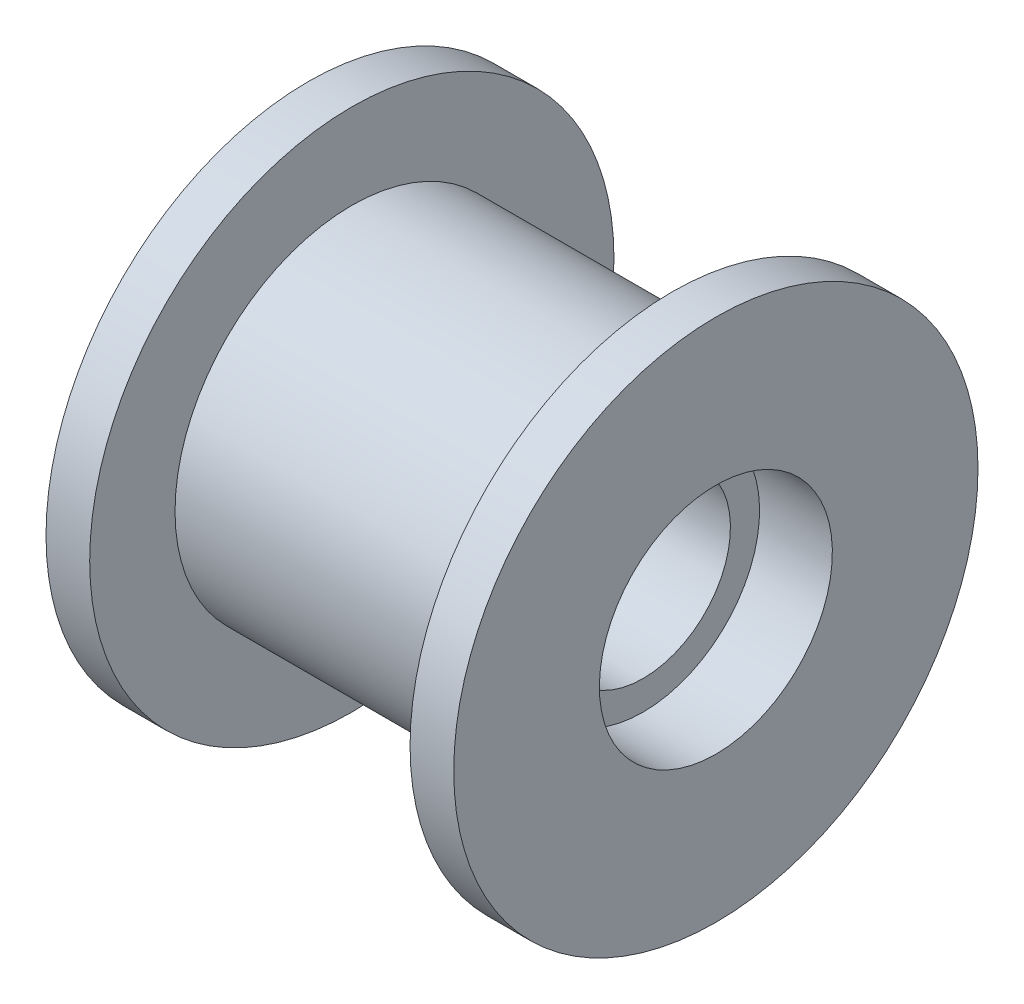
SolidWorks part; units mm, degrees
material "6061 Alloy"
ref_plane "Front Plane" through (0, 0, 0) normal (0, 0, 1) x (1, 0, 0)
ref_plane "Top Plane" through (0, 0, 0) normal (0, 1, 0) x (1, 0, 0)
ref_plane "Right Plane" through (0, 0, 0) normal (1, 0, 0) x (0, 0, -1)
sketch "Sketch1" plane through (0, 0, 0) normal (0, 0, 1) x (1, 0, 0)
  line L0 (-7, 0) -> (-7, 9)
  line L1 (-7, 9) -> (-5.5, 9)
  line L2 (-5.5, 9) -> (-5.5, 6.07)
  line L3 (-5.5, 6.07) -> (5.5, 6.07)
  line L4 (5.5, 6.07) -> (5.5, 9)
  line L5 (5.5, 9) -> (7, 9)
  line L6 (7, 9) -> (7, 0)
  line L7 (7, 0) -> (-7, 0)
  point P8 (0, 0)
  dimension "D1" = 9
  dimension "D2" = 1.5
  dimension "D3" = 2.93
  dimension "D4" = 11
  dimension "D5" = 1.5
revolve "Revolve1" add sketch "Sketch1" angle 360 about L7
sketch "Sketch3" plane through (7, 0, 0) normal (1, 0, 0) x (0, 0, -1)
  circle A0 centre (0, 0) radius 3
  dimension "D1" = 6
extrude "Cut-Extrude2" cut sketch "Sketch3" against normal through all both and the other way through all
sketch "Sketch2" plane through (-7, 0, 18.2091) normal (-1, 0, 0) x (0, 0, 1)
  circle A0 centre (-18.2091, 0) radius 4
  dimension "D1" = 8
extrude "Cut-Extrude1" cut sketch "Sketch2" against normal blind 2.5
sketch "Sketch4" plane through (7, 0, 11.2091) normal (-1, 0, 0) x (0, 0, 1)
  circle A0 centre (-11.2091, 0) radius 4
  dimension "D1" = 8
extrude "Cut-Extrude4" cut sketch "Sketch4" along normal blind 2.5
